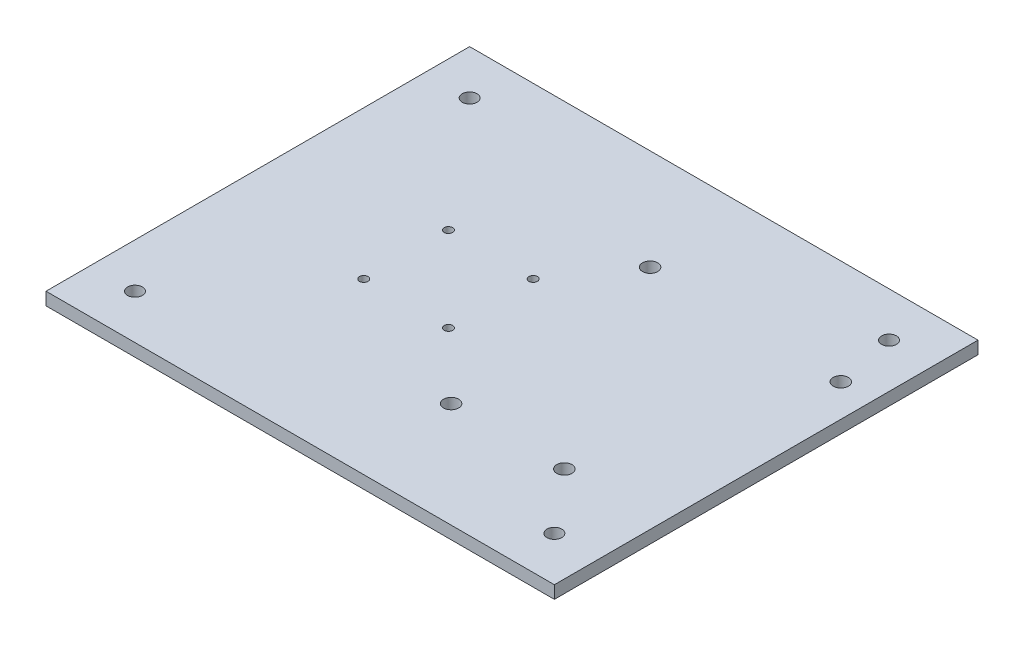
SolidWorks part; units mm, degrees
ref_plane "Front Plane" through (0, 0, 0) normal (0, 0, 1) x (1, 0, 0)
ref_plane "Top Plane" through (0, 0, 0) normal (0, 1, 0) x (1, 0, 0)
ref_plane "Right Plane" through (0, 0, 0) normal (1, 0, 0) x (0, 0, -1)
sketch "Sketch1" plane through (0, 0, 0) normal (0, 1, 0) x (1, 0, 0)
  line L1 (0, 0) -> (120, 0)
  line L2 (0, 0) -> (0, 100)
  line L3 (0, 100) -> (120, 100)
  line L4 (120, 0) -> (120, 100)
  dimension "D1" = 100
  dimension "D2" = 120
extrude "Boss-Extrude1" add sketch "Sketch1" along normal blind 3
sketch "Sketch2" plane through (0, 3, 0) normal (0, 1, 0) x (1, 0, 0)
  line L0 (10.5, 89.5) -> (109.5, 89.5) construction
  line L1 (10.5, 89.5) -> (10.5, 10.5) construction
  line L2 (10.5, 10.5) -> (109.5, 10.5) construction
  line L3 (109.5, 89.5) -> (109.5, 10.5) construction
  line L5 (60, 89.5) -> (60, 10.5) construction
  line L6 (0, 100) -> (120, 0) construction
  circle A0 centre (10.5, 89.5) radius 1.75
  circle A1 centre (109.5, 89.5) radius 1.75
  circle A2 centre (109.5, 10.5) radius 1.75
  circle A3 centre (10.5, 10.5) radius 1.75
  point P14 (60, 50)
  dimension "D3" = 3.5
  dimension "D1" = 99
  dimension "D2" = 79
extrude "holes_spacers" cut sketch "Sketch2" against normal blind 10
sketch "Sketch3" plane through (0, 3, 0) normal (0, 1, 0) x (1, 0, 0)
  line L0 (35, 60) -> (55, 60) construction
  line L1 (35, 60) -> (35, 40) construction
  line L2 (35, 40) -> (55, 40) construction
  line L3 (55, 60) -> (55, 40) construction
  line L4 (35, 60) -> (55, 40) construction
  line L5 (0, 100) -> (120, 0) construction
  line L6 (45, 50) -> (60, 50) construction
  circle A0 centre (35, 60) radius 1
  circle A1 centre (55, 60) radius 1
  circle A2 centre (55, 40) radius 1
  circle A3 centre (35, 40) radius 1
  point P12 (60, 50)
  point P13 (45, 50)
  point P16 (47.1074, 49.3005)
  dimension "D3" = 2
  dimension "D1" = 20
  dimension "D2" = 20
  dimension "D4" = 15
extrude "holes_IMU" cut sketch "Sketch3" against normal up to next
sketch "Sketch4" plane through (0, 3, 0) normal (0, 1, 0) x (1, 0, 0)
  line L0 (66.3897, 76.2074) -> (112.3297, 76.2074) construction
  line L1 (112.3297, 76.2074) -> (112.3297, 75.2874) construction
  line L2 (112.3297, 75.2874) -> (112.3297, 24.8374) construction
  line L3 (112.3297, 24.8374) -> (97.5197, 24.8374) construction
  line L4 (97.5197, 24.8374) -> (70.7797, 24.8374) construction
  circle A0 centre (66.3897, 76.2074) radius 1.8
  circle A1 centre (112.3297, 75.2874) radius 1.8
  circle A2 centre (97.5197, 24.8374) radius 1.8
  circle A3 centre (70.7797, 24.8374) radius 1.8
  dimension "D2" = 3.6
  dimension "D1" = 0.92
  dimension "D3" = 50.45
  dimension "D4" = 14.81
  dimension "D5" = 26.74
extrude "holes_arduino" cut sketch "Sketch4" against normal up to next
